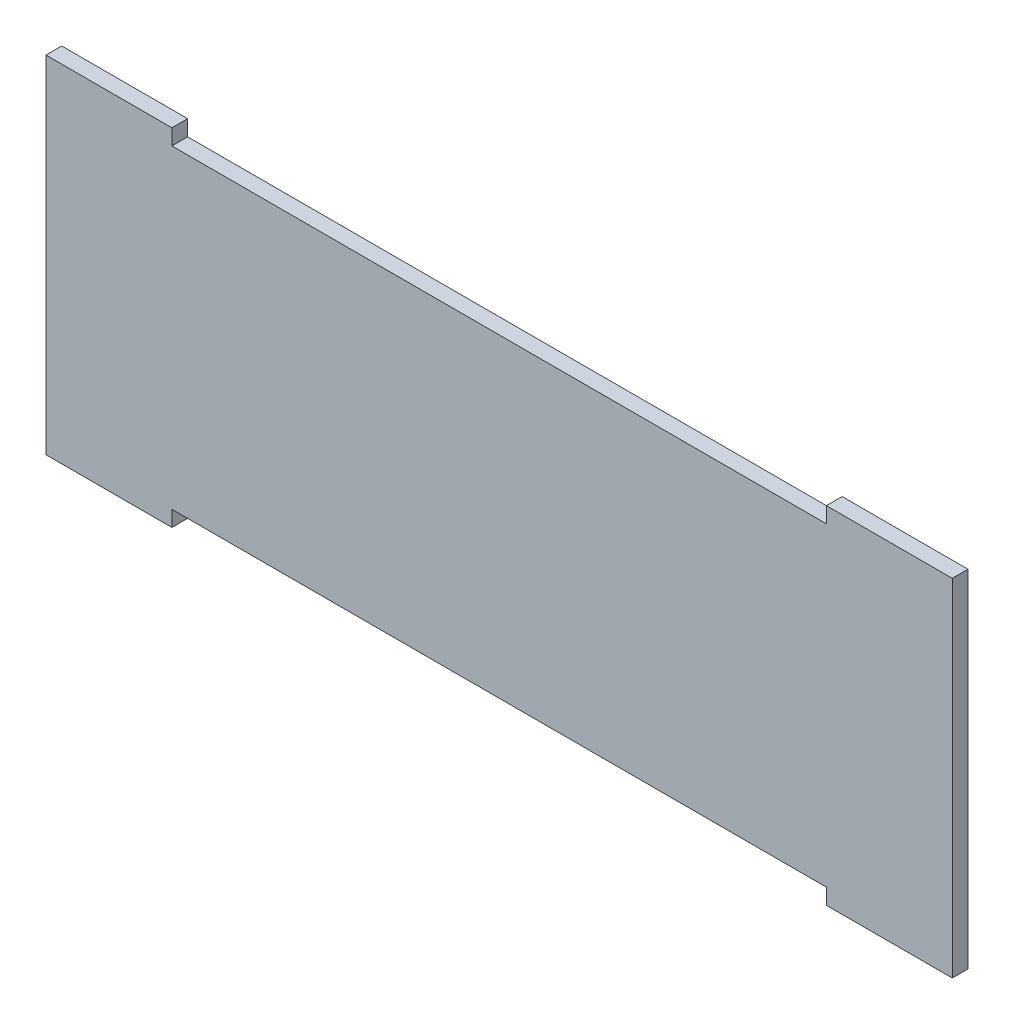
SolidWorks part; units mm, degrees
ref_plane "Front Plane" through (0, 0, 0) normal (0, 0, 1) x (1, 0, 0)
ref_plane "Top Plane" through (0, 0, 0) normal (0, 1, 0) x (1, 0, 0)
ref_plane "Right Plane" through (0, 0, 0) normal (1, 0, 0) x (0, 0, -1)
sketch "Sketch2" plane through (0, 0, 0) normal (0, 0, 1) x (1, 0, 0)
  line L0 (-75.4551, 48.8404) -> (-50.0551, 48.8404)
  line L1 (82.0249, 48.8404) -> (107.4249, 48.8404)
  line L2 (-75.4551, 48.8404) -> (-75.4551, -21.0096)
  line L4 (107.4249, 48.8404) -> (107.4249, -21.0096)
  line L5 (-75.4551, -21.0096) -> (-50.0551, -21.0096)
  line L6 (-50.0551, 48.8404) -> (-50.0551, 45.6654)
  line L7 (-50.0551, 45.6654) -> (82.0249, 45.6654)
  line L8 (82.0249, 48.8404) -> (82.0249, 45.6654)
  line L10 (-50.0551, -21.0096) -> (-50.0551, -17.8346)
  line L11 (-50.0551, -17.8346) -> (82.0249, -17.8346)
  line L12 (82.0249, -21.0096) -> (82.0249, -17.8346)
  line L13 (82.0249, -21.0096) -> (107.4249, -21.0096)
  dimension "D1" = 182.88
  dimension "D2" = 69.85
  dimension "D3" = 25.4
  dimension "D4" = 25.4
  dimension "D5" = 3.175
  dimension "D6" = 25.4
  dimension "D7" = 25.4
  dimension "D8" = 3.175
extrude "Boss-Extrude1" add sketch "Sketch2" along normal blind 3.175
